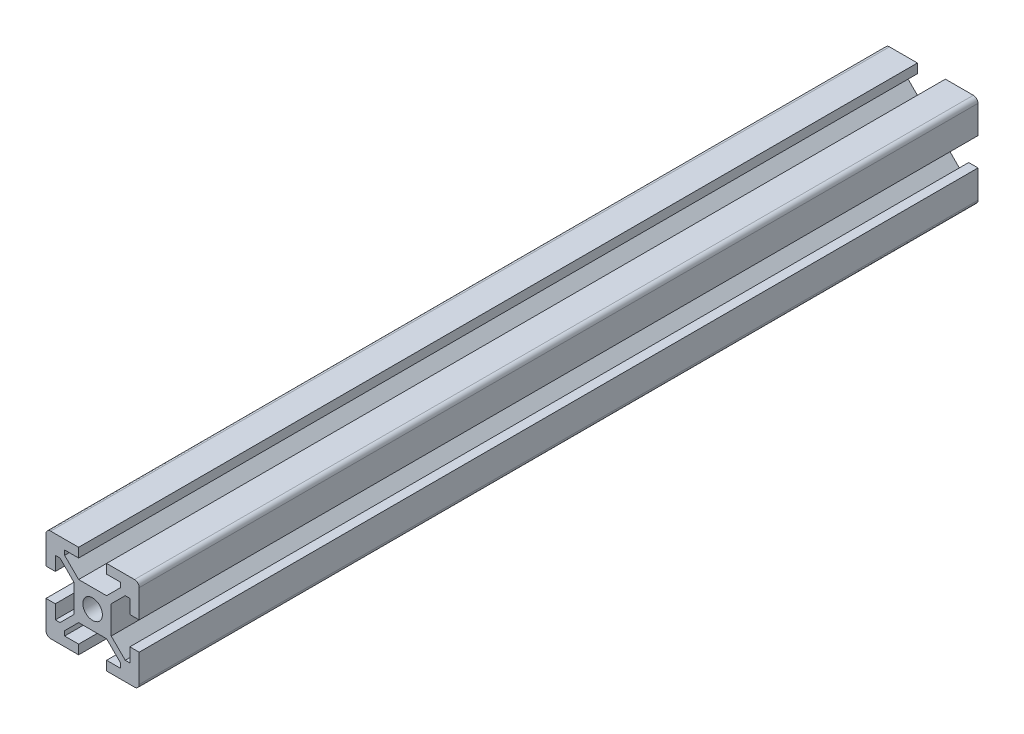
SolidWorks part; units mm, degrees
material "6063-T5"
ref_plane "Front Plane" through (0, 0, 0) normal (0, 0, 1) x (1, 0, 0)
ref_plane "Top Plane" through (0, 0, 0) normal (0, 1, 0) x (1, 0, 0)
ref_plane "Right Plane" through (0, 0, 0) normal (1, 0, 0) x (0, 0, -1)
ref_plane "Plane1" through (0, 0, 0) normal (0, 0, -1) x (-1, 0, 0)
sketch "Sketch1" plane through (0, 0, 0) normal (0, 0, -1) x (-1, 0, 0)
  line L0 (6, -8) -> (3, -8)
  line L1 (3, -8) -> (3, -10)
  line L2 (3, -10) -> (9, -10)
  line L3 (10, -9) -> (10, -3)
  line L4 (10, -3) -> (8, -3)
  line L5 (8, -3) -> (8, -6)
  line L6 (8, -6) -> (7, -6)
  line L7 (7, -6) -> (4, -3)
  line L8 (4, -3) -> (4, 3)
  line L9 (4, 3) -> (7, 6)
  line L10 (7, 6) -> (8, 6)
  line L11 (8, 6) -> (8, 3)
  line L12 (8, 3) -> (10, 3)
  line L13 (10, 3) -> (10, 9)
  line L14 (9, 10) -> (3, 10)
  line L15 (3, 10) -> (3, 8)
  line L16 (3, 8) -> (6, 8)
  line L17 (6, 8) -> (6, 7)
  line L18 (6, 7) -> (3, 4)
  line L19 (3, 4) -> (-3, 4)
  line L20 (-3, 4) -> (-6, 7)
  line L21 (-6, 7) -> (-6, 8)
  line L22 (-6, 8) -> (-3, 8)
  line L23 (-3, 8) -> (-3, 10)
  line L24 (-3, 10) -> (-9, 10)
  line L25 (-10, 9) -> (-10, 3)
  line L26 (-10, 3) -> (-8, 3)
  line L27 (-8, 3) -> (-8, 6)
  line L28 (-8, 6) -> (-7, 6)
  line L29 (-7, 6) -> (-4, 3)
  line L30 (-4, 3) -> (-4, -3)
  line L31 (-4, -3) -> (-7, -6)
  line L32 (-7, -6) -> (-8, -6)
  line L33 (-8, -6) -> (-8, -3)
  line L34 (-8, -3) -> (-10, -3)
  line L35 (-10, -3) -> (-10, -9)
  line L36 (-9, -10) -> (-3, -10)
  line L37 (-3, -10) -> (-3, -8)
  line L38 (-3, -8) -> (-6, -8)
  line L39 (-6, -8) -> (-6, -7)
  line L40 (-6, -7) -> (-3, -4)
  line L41 (-3, -4) -> (3, -4)
  line L42 (3, -4) -> (6, -7)
  line L43 (6, -7) -> (6, -8)
  line L44 (0, 4) -> (0, 0) construction
  line L45 (0, 0) -> (-4, 0) construction
  line L46 (0, 0) -> (4, 0) construction
  line L47 (0, 0) -> (0, -4) construction
  circle A0 centre (0, 0) radius 2.1
  arc A1 (9, -10) -> (10, -9) centre (9, -9) ccw
  arc A2 (10, 9) -> (9, 10) centre (9, 9) ccw
  arc A3 (-9, 10) -> (-10, 9) centre (-9, 9) ccw
  arc A4 (-10, -9) -> (-9, -10) centre (-9, -9) ccw
  dimension "D6" = 1
  dimension "D10" = 4.2
  dimension "D1" = 10
  dimension "D2" = 10
  dimension "D3" = 10
  dimension "D4" = 10
  dimension "D5" = 8
  dimension "D7" = 2
  dimension "D8" = 7
  dimension "D9" = 8
  dimension "D11" = 1
  dimension "D12" = 1
  dimension "D13" = 2
  dimension "D14" = 3
  dimension "D15" = 2
  dimension "D16" = 1
  dimension "D17" = 1
  dimension "D18" = 4.2426
  dimension "D19" = 6
  dimension "D20" = 7
extrude "Boss-Extrude1" add sketch "Sketch1" against normal blind 180
ref_plane "Plane2" through (0, 0, 0) normal (1, 0, 0) x (0, 0, -1)
